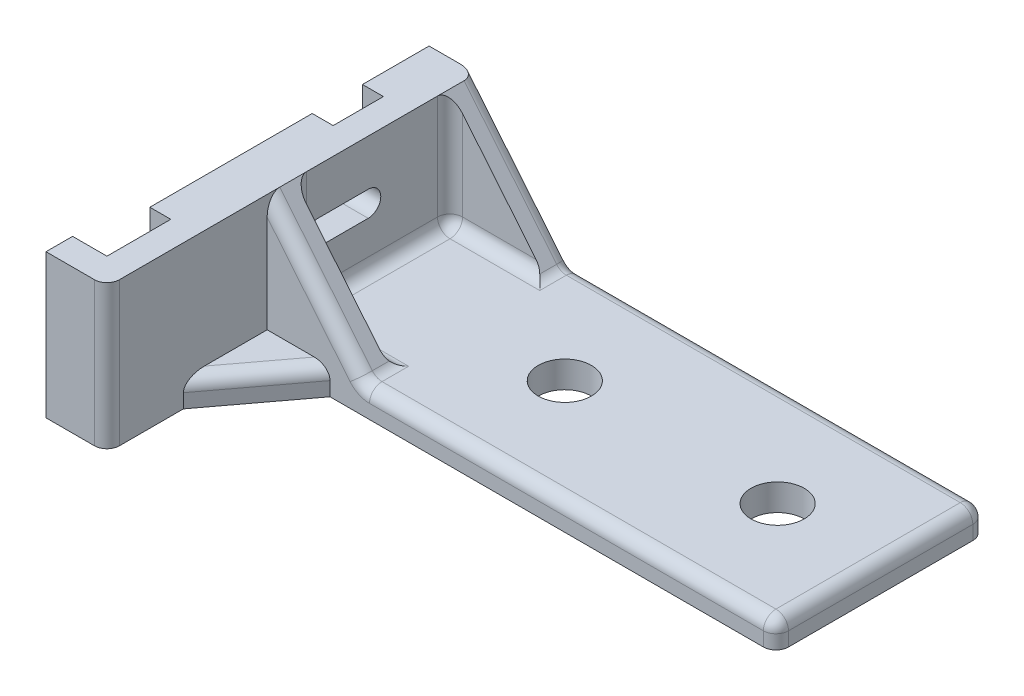
SolidWorks part; units mm, degrees
material "ABS"
ref_plane "Front Plane" through (0, 0, 0) normal (0, 0, 1) x (1, 0, 0)
ref_plane "Top Plane" through (0, 0, 0) normal (0, 1, 0) x (1, 0, 0)
ref_plane "Right Plane" through (0, 0, 0) normal (1, 0, 0) x (0, 0, -1)
sketch "Sketch2" plane through (0, 0, 0) normal (0, 1, 0) x (1, 0, 0)
  line L0 (12.7, 0) -> (-12.7, 0) construction
  line L1 (25, -12.5) -> (25, 12.5)
  line L2 (25, -12.5) -> (-25, -12.5)
  line L3 (-25, -12.5) -> (-25, 12.5)
  line L4 (25, 12.5) -> (-25, 12.5)
  line L5 (25, -12.5) -> (-25, 12.5) construction
  line L6 (-25, -12.5) -> (25, 12.5) construction
  circle A0 centre (-12.7, 0) radius 3.175
  circle A1 centre (12.7, 0) radius 3.175
  circle A3 centre (-12.7, 0) radius 6.985 construction
  point P0 (0, 0)
  point P9 (0, 0)
  dimension "D1" = 25
  dimension "D2" = 50
extrude "Boss-Extrude1" add sketch "Sketch2" along normal blind 3.175
sketch "Sketch11" plane through (0, 0, 0) normal (0, 1, 0) x (1, 0, 0)
  line L1 (-25, -12.5) -> (-43, -12.5)
  line L2 (-25, -12.5) -> (-25, 12.5)
  line L3 (-25, 12.5) -> (-43, 12.5)
  line L4 (-43, -12.5) -> (-43, 12.5)
  dimension "D1" = 18
extrude "Boss-Extrude4" add sketch "Sketch11" along normal blind 3.175
sketch "Sketch12" plane through (-43, 0, 0) normal (-1, 0, 0) x (0, 0, 1)
  line L1 (-12.5, 0) -> (31.625, 0)
  line L2 (-12.5, 0) -> (-12.5, 17.175)
  line L3 (-12.5, 17.175) -> (31.625, 17.175)
  line L4 (31.625, 0) -> (31.625, 17.175)
  dimension "D1" = 17.175
  dimension "D2" = 31.625
extrude "Boss-Extrude5" add sketch "Sketch12" against normal blind 7.275
sketch "Sketch13" plane through (-43, 0, 0) normal (-1, 0, 0) x (0, 0, 1)
  line L0 (31.625, 0) -> (31.625, 17.175) construction
  line L1 (28.45, 3.175) -> (-16.9109, 3.175)
  line L2 (28.45, 3.175) -> (28.45, 25.8701)
  line L3 (28.45, 25.8701) -> (-16.9109, 25.8701)
  line L4 (-16.9109, 3.175) -> (-16.9109, 25.8701)
  line L5 (-12.5, 0) -> (31.625, 0) construction
  dimension "D1" = 3.175
  dimension "D2" = 3.175
extrude "Cut-Extrude1" cut sketch "Sketch13" against normal blind 1.6
sketch "Sketch14" plane through (-41.4, 0, 0) normal (-1, 0, 0) x (0, 0, 1)
  line L0 (28.45, 10.175) -> (6.45, 10.175) construction
  line L1 (28.45, 3.175) -> (28.45, 17.175) construction
  line L2 (6.45, 10.175) -> (0.4426, 10.175) construction
  line L3 (6.45, 8.675) -> (0.4426, 8.675)
  line L4 (6.45, 11.675) -> (0.4426, 11.675)
  arc A1 (6.45, 8.675) -> (6.45, 11.675) centre (6.45, 10.175) ccw
  arc A2 (0.4426, 11.675) -> (0.4426, 8.675) centre (0.4426, 10.175) ccw
  point P4 (3.4463, 10.175)
  point P10 (6.5382, 10.175)
  point P11 (0.4426, 10.175)
extrude "Cut-Extrude2" cut sketch "Sketch14" against normal through all
sketch "Sketch15" plane through (0, 0, -12.5) normal (0, 0, -1) x (-1, 0, 0)
  line L0 (35.725, 17.175) -> (24.225, 3.175)
  line L1 (-25, 3.175) -> (35.725, 3.175) construction
  line L2 (24.225, 3.175) -> (35.725, 3.175)
  line L3 (35.725, 3.175) -> (35.725, 17.175)
extrude "Boss-Extrude6" add sketch "Sketch15" against normal blind 3.175
mirror "Mirror1" about plane through (0, 0, 0) normal (0, 0, 1) of "Boss-Extrude6"
sketch "Sketch16" plane through (0, 0, 0) normal (0, -1, 0) x (1, 0, 0)
  line L0 (-35.725, 12.5) -> (-28.225, 12.5)
  line L1 (-35.725, 12.5) -> (25, 12.5) construction
  line L2 (-28.225, 12.5) -> (-35.725, 22.5)
  line L3 (-35.725, 12.5) -> (-35.725, 31.625) construction
  line L4 (-35.725, 12.5) -> (-35.725, 22.5)
extrude "Boss-Extrude7" add sketch "Sketch16" against normal blind 3.175
fillet "Fillet7" radius 1.5 16 edges at (-29.975, 10.175, 12.5) (-29.975, 10.175, -12.5) (0.3875, 3.175, 12.5) (25, 1.5875, 12.5) (25, 3.175, 0) (25, 1.5875, -12.5) (0.3875, 3.175, -12.5) (-35.725, 10.175, -9.325) (-29.975, 3.175, -9.325) (-29.975, 3.175, 9.325) (-35.725, 10.175, 9.325) (-35.725, 3.175, 0) (-31.975, 3.175, 17.5) (-24.225, 3.175, -10.9125) (-24.225, 3.175, 10.9125) (-35.725, 8.5875, 31.625)
sketch "Sketch17" plane through (0, 17.175, 0) normal (0, 1, 0) x (1, 0, 0)
  line L0 (-41.4, -28.45) -> (-41.4, 4.55) construction
  line L1 (-41.4, -28.45) -> (-38.9, -28.45)
  line L2 (-41.4, -28.45) -> (-41.4, -20.83)
  line L3 (-41.4, -20.83) -> (-38.9, -20.83)
  line L4 (-38.9, -28.45) -> (-38.9, -20.83)
  line L5 (-41.4, 12.5) -> (-41.4, -28.45) construction
  line L7 (-41.4, 4.55) -> (-38.9, 4.55)
  line L8 (-41.4, 4.55) -> (-41.4, -1.45)
  line L9 (-41.4, -1.45) -> (-38.9, -1.45)
  line L10 (-38.9, 4.55) -> (-38.9, -1.45)
  dimension "D1" = 2.5
  dimension "D2" = 7.62
  dimension "D3" = 6
extrude "Cut-Extrude3" cut sketch "Sketch17" against normal blind 14
